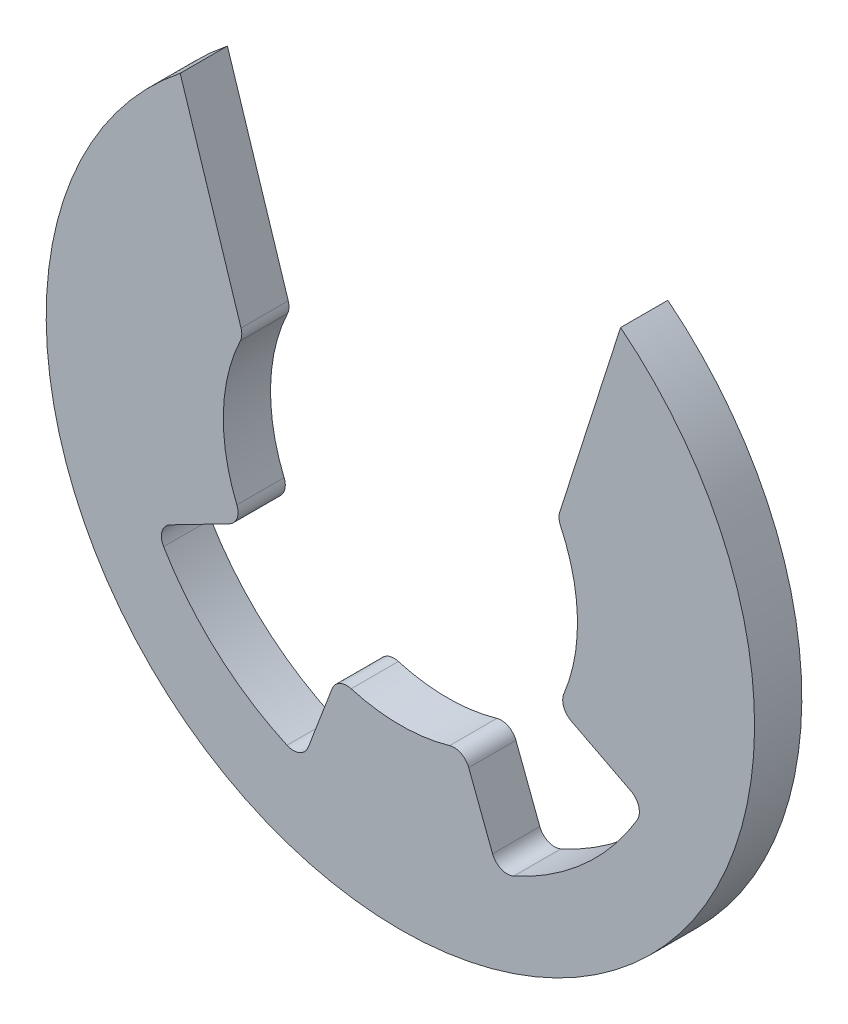
SolidWorks part; units mm, degrees
ref_plane "Front Plane" through (0, 0, 0) normal (0, 0, 1) x (1, 0, 0)
ref_plane "Top Plane" through (0, 0, 0) normal (0, 1, 0) x (1, 0, 0)
ref_plane "Right Plane" through (0, 0, 0) normal (1, 0, 0) x (0, 0, -1)
sketch "Sketch1" plane through (0, 0, 0) normal (0, 0, 1) x (1, 0, 0)
  line L0 (0, 4.5) -> (0, -4.5) construction
  line L1 (2.7976, 3.5247) -> (2.0246, 1.1077)
  line L2 (0.8682, -2.2823) -> (1.1712, -3.0787)
  line L3 (2.1705, -1.1187) -> (2.9279, -1.509)
  line L4 (2, 1.0308) -> (2.46, 0.1382) construction
  line L5 (-0.8682, -2.2823) -> (-1.1712, -3.0787)
  line L6 (-2.1705, -1.1187) -> (-2.9279, -1.509)
  line L7 (-2.7976, 3.5247) -> (-2.0246, 1.1077)
  arc A0 (-2.7976, 3.5247) -> (2.7976, 3.5247) centre (0, 0) ccw
  arc A1 (-0.6257, -2.1613) -> (0.6257, -2.1613) centre (0, 0) ccw
  arc A3 (2.0775, -0.8641) -> (2.0343, 0.9614) centre (0, 0) ccw
  arc A4 (1.4404, -3.1899) -> (3.0082, -1.789) centre (0, 0) ccw
  arc A5 (2.0246, 1.1077) -> (2.0343, 0.9614) centre (2.2151, 1.0468) ccw
  arc A6 (2.1705, -1.1187) -> (2.0775, -0.8641) centre (2.2621, -0.9409) cw
  arc A7 (0.8682, -2.2823) -> (0.6257, -2.1613) centre (0.6813, -2.3534) ccw
  arc A8 (1.1712, -3.0787) -> (1.4404, -3.1899) centre (1.3581, -3.0076) ccw
  arc A9 (2.9279, -1.509) -> (3.0082, -1.789) centre (2.8363, -1.6868) cw
  arc A10 (-0.8682, -2.2823) -> (-0.6257, -2.1613) centre (-0.6813, -2.3534) cw
  arc A11 (-1.1712, -3.0787) -> (-1.4404, -3.1899) centre (-1.3581, -3.0076) cw
  arc A12 (-1.4404, -3.1899) -> (-3.0082, -1.789) centre (0, 0) cw
  arc A13 (-2.9279, -1.509) -> (-3.0082, -1.789) centre (-2.8363, -1.6868) ccw
  arc A14 (-2.1705, -1.1187) -> (-2.0775, -0.8641) centre (-2.2621, -0.9409) ccw
  arc A15 (-2.0775, -0.8641) -> (-2.0343, 0.9614) centre (0, 0) cw
  arc A16 (-2.0246, 1.1077) -> (-2.0343, 0.9614) centre (-2.2151, 1.0468) cw
  point P17 (2, -1.0308)
  point P20 (0.8, -2.103)
  dimension "D1" = 9
  dimension "D2" = 4.5
  dimension "D3" = 3.5
  dimension "D8" = 0.2
  dimension "D4" = 0.8
  dimension "D5" = 2
  dimension "D6" = 135
  dimension "D7" = 2
extrude "Boss-Extrude1" add sketch "Sketch1" along normal blind 0.6
